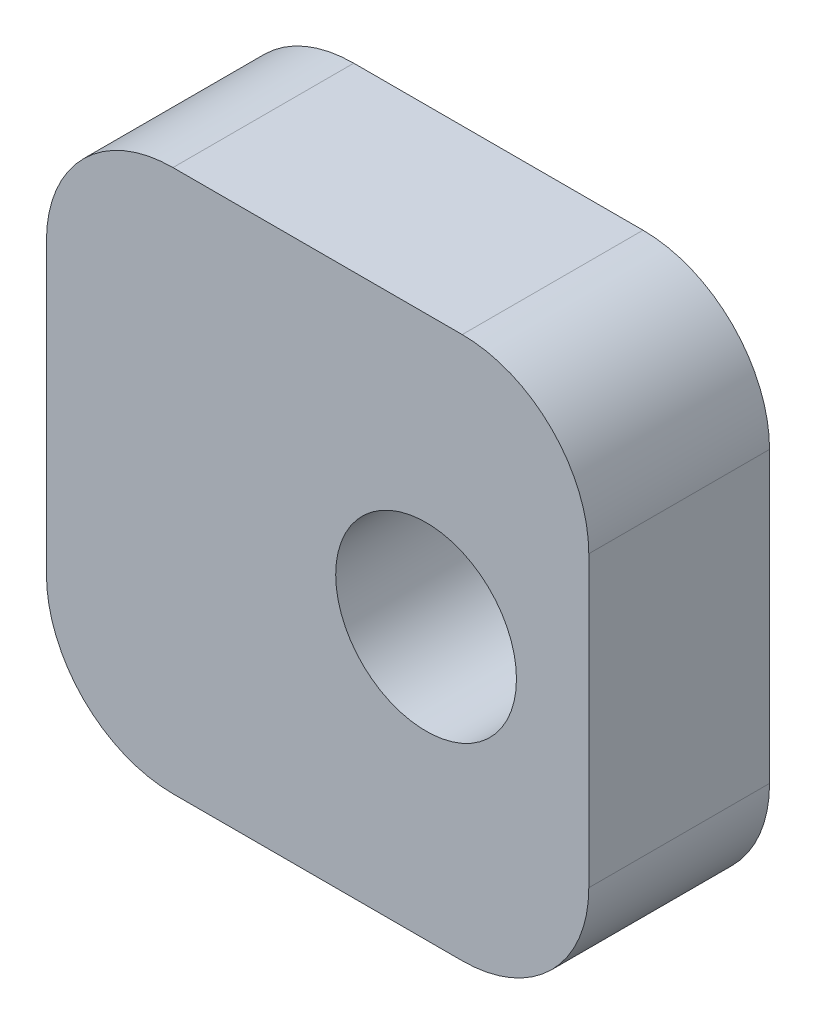
SolidWorks part; units mm, degrees
ref_plane "前视基准面" through (0, 0, 0) normal (0, 0, 1) x (1, 0, 0)
ref_plane "上视基准面" through (0, 0, 0) normal (0, 1, 0) x (1, 0, 0)
ref_plane "右视基准面" through (0, 0, 0) normal (1, 0, 0) x (0, 0, -1)
other "Configuration Table"
sketch "草图1" plane through (0, 0, 0) normal (0, 0, 1) x (1, 0, 0)
  line L1 (0, 0) -> (30, 0)
  line L2 (0, 0) -> (0, 30)
  line L3 (0, 30) -> (30, 30)
  line L4 (30, 0) -> (30, 30)
  dimension "D1" = 30
  dimension "D2" = 30
extrude "凸台-拉伸1" add sketch "草图1" along normal blind 10
sketch "草图2" plane through (0, 0, 0) normal (0, 0, -1) x (-1, 0, 0)
  line L0 (-30, 15) -> (0, 15) construction
  line L1 (-30, 0) -> (-30, 30) construction
  line L2 (0, 30) -> (0, 0) construction
  circle A0 centre (-21, 15) radius 5
  dimension "D1" = 10
  dimension "D2" = 9
extrude "切除-拉伸1" cut sketch "草图2" against normal up to next
fillet "圆角1" radius 7 4 edges at (30, 30, 5) (0, 30, 5) (0, 0, 5) (30, 0, 5)
sketch "草图3" plane through (0, 0, 0) normal (-1, 0, 0) x (0, 0, 1)
  line L0 (0, 15) -> (10, 15) construction
  line L1 (0, 23) -> (0, 7) construction
  line L2 (10, 23) -> (10, 7) construction
  circle A0 centre (5, 15) radius 3
  dimension "D1" = 6
extrude "切除-拉伸2" cut sketch "草图3" against normal blind 12
